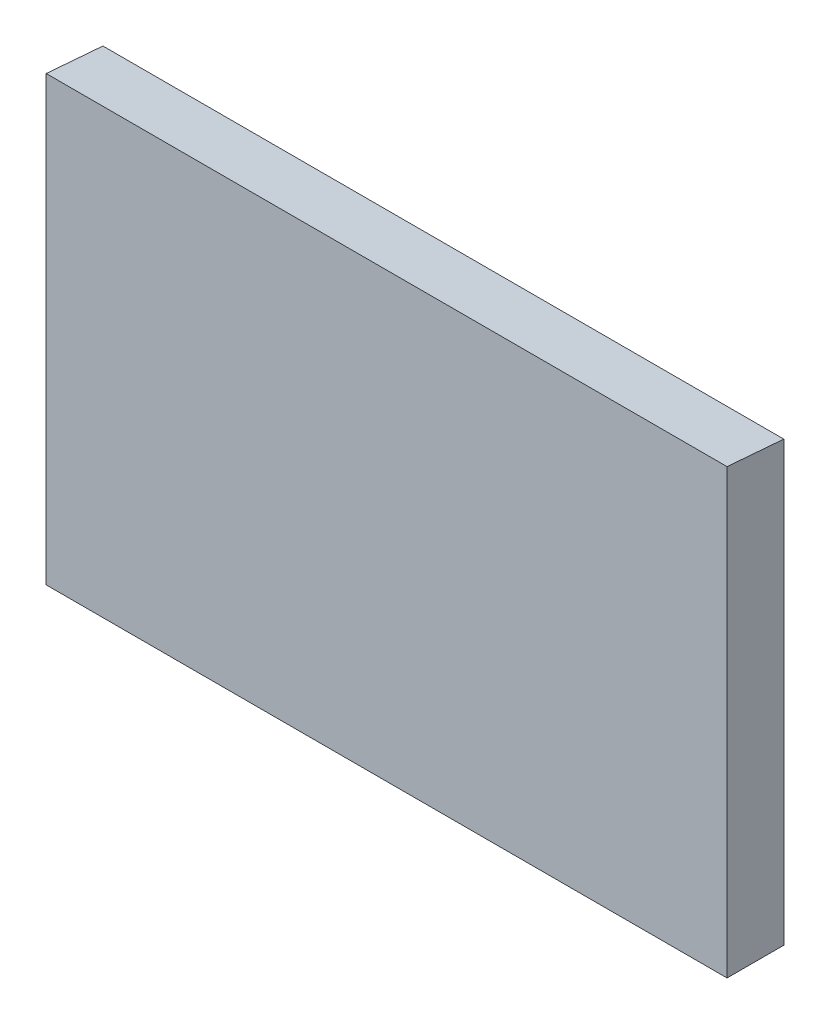
SolidWorks part; units mm, degrees
material "Cedro"
ref_plane "Alzado" through (0, 0, 0) normal (0, 0, 1) x (1, 0, 0)
ref_plane "Planta" through (0, 0, 0) normal (0, 1, 0) x (1, 0, 0)
ref_plane "Vista lateral" through (0, 0, 0) normal (1, 0, 0) x (0, 0, -1)
sketch "Croquis1" plane through (0, 0, 0) normal (1, 0, 0) x (0, 0, -1)
  line L1 (-7.5, -57.84) -> (7.5, -57.84)
  line L2 (-7.5, -57.84) -> (-7.5, 57.84)
  line L3 (-7.5, 57.84) -> (7.5, 57.84)
  line L4 (7.5, -57.84) -> (7.5, 57.84)
  line L5 (-7.5, -57.84) -> (7.5, 57.84) construction
  line L6 (-7.5, 57.84) -> (7.5, -57.84) construction
  point P0 (0, 0)
  dimension "D1" = 15
  dimension "D2" = 115.68
extrude "Saliente-Extruir1" add sketch "Croquis1" along normal blind 180
sketch "Croquis3" plane through (180, 0, 0) normal (1, 0, 0) x (0, 0, -1)
  line L2 (7.5, 57.84) -> (-7.5, 57.84)
  line L3 (-7.5, 57.84) -> (-7.5, 59.24)
  line L5 (7.5, 57.84) -> (7.5, 58.04)
  line L6 (7.5, 58.04) -> (-7.5, 59.24)
  dimension "D1" = 1.4
  dimension "D2" = 0.2
extrude "Saliente-Extruir3" add sketch "Croquis3" against normal through all
